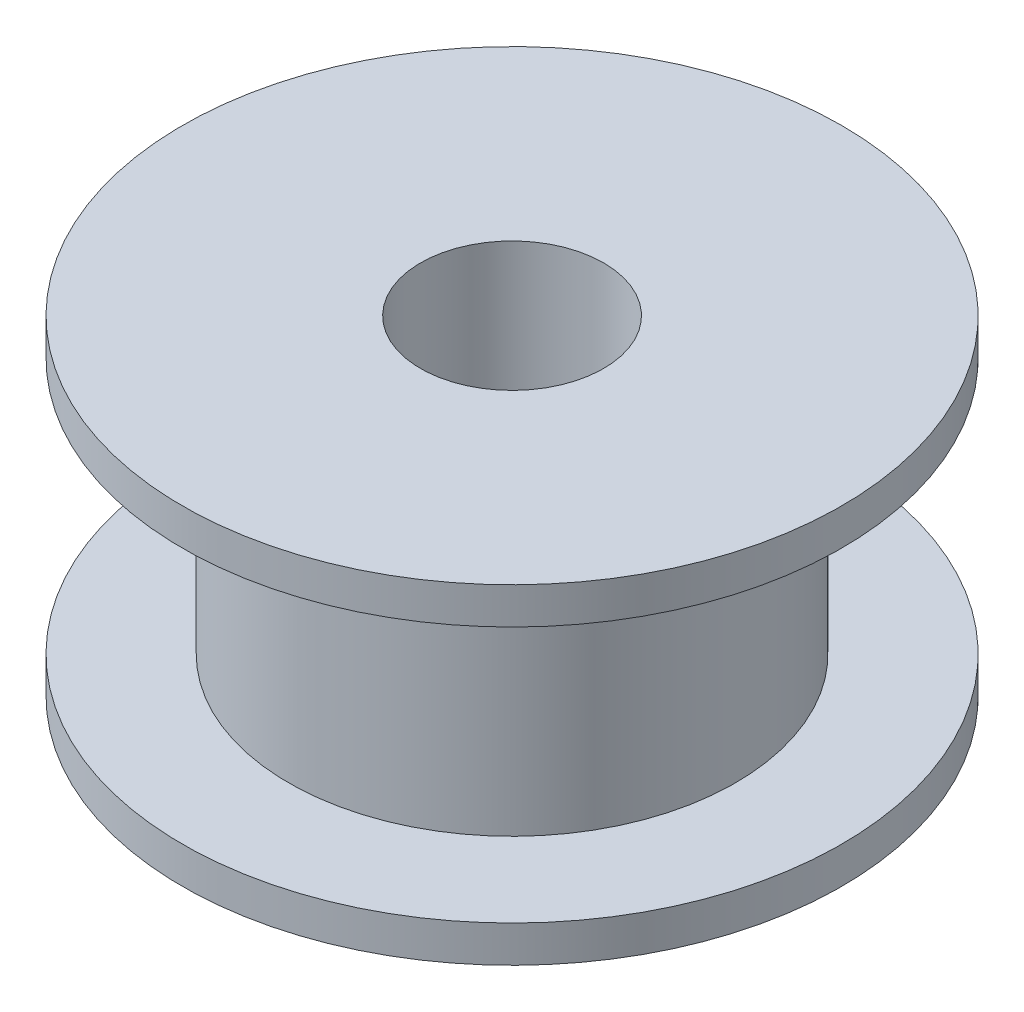
SolidWorks part; units mm, degrees
ref_plane "Front Plane" through (0, 0, 0) normal (0, 0, 1) x (1, 0, 0)
ref_plane "Top Plane" through (0, 0, 0) normal (0, 1, 0) x (1, 0, 0)
ref_plane "Right Plane" through (0, 0, 0) normal (1, 0, 0) x (0, 0, -1)
sketch "Sketch1" plane through (0, 0, 0) normal (0, 0, 1) x (1, 0, 0)
  line L1 (9.9, 0) -> (-9.9, 0) construction
  line L2 (9, 0) -> (9, 1)
  line L3 (9, 1) -> (6.1, 1)
  line L4 (6.1, 1) -> (6.1, 8)
  line L5 (6.1, 8) -> (9, 8)
  line L6 (9, 8) -> (9, 9)
  line L10 (9, 0) -> (2.5, 0)
  line L11 (2.5, 0) -> (2.5, 9)
  line L12 (2.5, 9) -> (9, 9)
  line L13 (0, -4.95) -> (0, 4.95) construction
  point P0 (6.1, 4.5)
  point P12 (2.5, 4.5)
  dimension "D1" = 9
  dimension "D2" = 2.5
  dimension "D3" = 6.1
  dimension "D4" = 9
  dimension "D5" = 1
ref_axis "Axis1" through (0, -0.45, 0) along (0, 1, 0)
revolve "Revolve1" add sketch "Sketch1" angle 360 about axis through (0, -0.45, 0) along (0, 1, 0)
